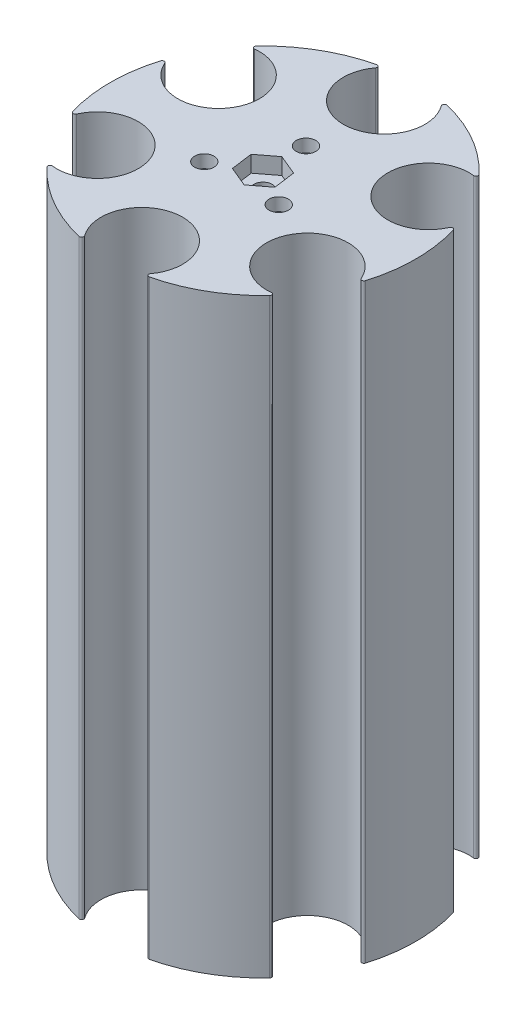
SolidWorks part; units mm, degrees
ref_plane "Front Plane" through (0, 0, 0) normal (0, 0, 1) x (1, 0, 0)
ref_plane "Top Plane" through (0, 0, 0) normal (0, 1, 0) x (1, 0, 0)
ref_plane "Right Plane" through (0, 0, 0) normal (1, 0, 0) x (0, 0, -1)
sketch "Sketch1" plane through (0, 0, 0) normal (0, 1, 0) x (1, 0, 0)
  circle A0 centre (0, 0) radius 35.56
  dimension "D1" = 71.12
extrude "Boss-Extrude1" add sketch "Sketch1" along normal mid plane 137.5
sketch "Sketch2" plane through (0, 68.75, 0) normal (0, 1, 0) x (1, 0, 0)
  line L0 (0, 35.56) -> (0, -35.56) construction
  line L1 (-35.56, 0) -> (35.56, 0) construction
  circle A0 centre (0, 0) radius 35.56 construction
  circle A1 centre (0, 28.2) radius 9.5
  dimension "D1" = 19
  dimension "D2" = 28.2
extrude "Cut-Extrude1" cut sketch "Sketch2" against normal through all
pattern_circular "CirPattern1" count 6 over 360 about axis through (0, 0, 0) along (0, 1, 0) of "Cut-Extrude1"
sketch "Sketch3" plane through (0, 68.75, 0) normal (0, 1, 0) x (1, 0, 0)
  line L0 (0, 18.7) -> (0, -18.7) construction
  arc A0 (-6.7148, 34.9203) -> (6.7148, 34.9203) centre (0, 28.2) ccw construction
  arc A1 (6.7148, -34.9203) -> (-6.7148, -34.9203) centre (0, -28.2) ccw construction
  circle A2 centre (0, 10) radius 2.25
  dimension "D2" = 4.5
  dimension "D1" = 10
extrude "Cut-Extrude2" cut sketch "Sketch3" against normal blind 3
pattern_circular "CirPattern2" count 3 over 360 about axis through (0, 0, 0) along (0, 1, 0) of "Cut-Extrude2"
sketch "Sketch4" plane through (0, 68.75, 0) normal (0, 1, 0) x (1, 0, 0)
  line L1 (0.6607, -5.0375) -> (4.693, -1.9466)
  line L2 (4.693, -1.9466) -> (4.0323, 3.091)
  line L3 (4.0323, 3.091) -> (-0.6607, 5.0375)
  line L4 (-0.6607, 5.0375) -> (-4.693, 1.9466)
  line L5 (-4.693, 1.9466) -> (-4.0323, -3.091)
  line L6 (-4.0323, -3.091) -> (0.6607, -5.0375)
  circle A2 centre (0, 0) radius 4.4 construction
  dimension "D1" = 8.8
extrude "Cut-Extrude3" cut sketch "Sketch4" against normal blind 3.81
sketch "Sketch5" plane through (0, 64.94, 0) normal (0, 1, 0) x (1, 0, 0)
  circle A0 centre (0, 0) radius 2.159
  dimension "D1" = 4.318
extrude "Cut-Extrude4" cut sketch "Sketch5" against normal blind 7.62
mirror "Mirror3" about plane through (0, 0, 0) normal (0, 1, 0) of "Cut-Extrude2", "CirPattern2", "Cut-Extrude4", "Cut-Extrude3"
fillet "Fillet1" radius 0.5 12 edges at (26.8845, 0, -23.2753) (33.5992, 0, -11.645) (33.5992, 0, 11.645) (26.8845, 0, 23.2753) (6.7148, 0, 34.9203) (-6.7148, 0, 34.9203) (-26.8845, 0, 23.2753) (-33.5992, 0, 11.645) (-33.5992, 0, -11.645) (-26.8845, 0, -23.2753) (-6.7148, 0, -34.9203) (6.7148, 0, -34.9203)
